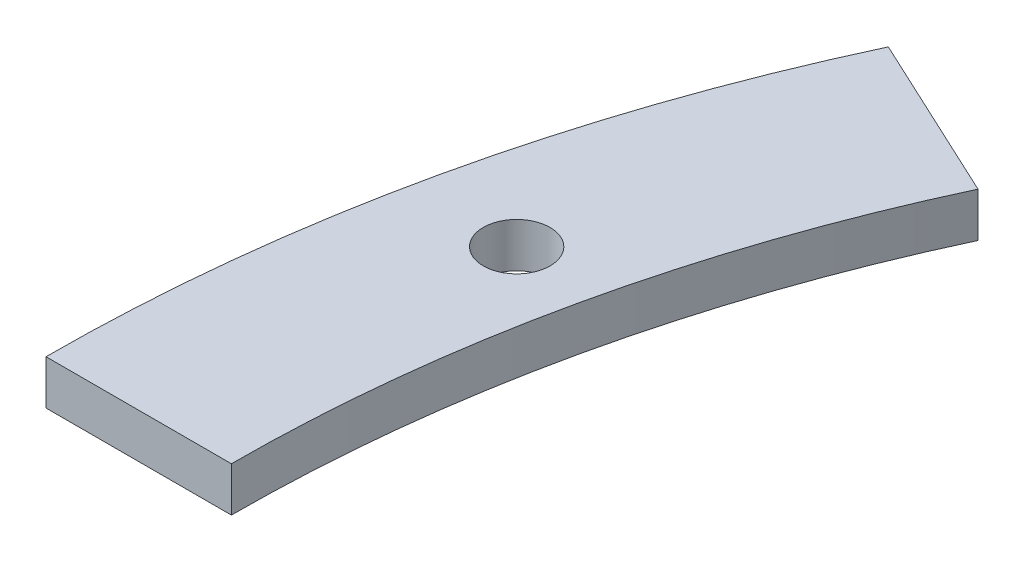
SolidWorks part; units mm, degrees
material "ABS"
ref_plane "Piano frontale" through (0, 0, 0) normal (0, 0, 1) x (1, 0, 0)
ref_plane "Piano superiore" through (0, 0, 0) normal (0, 1, 0) x (1, 0, 0)
ref_plane "Piano destro" through (0, 0, 0) normal (1, 0, 0) x (0, 0, -1)
sketch "Schizzo1" plane through (0, 0, 0) normal (0, 1, 0) x (1, 0, 0)
  line L0 (0, 0) -> (-110, 0) construction
  line L1 (0, 0) -> (-99.6939, 46.488) construction
  line L2 (-99.6939, 46.488) -> (-88.365, 41.2053)
  line L3 (-110, 0) -> (-97.5, 0)
  arc A0 (-88.365, 41.2053) -> (-97.5, 0) centre (0, 0) ccw
  arc A1 (-99.6939, 46.488) -> (-110, 0) centre (0, 0) ccw
  dimension "D1" = 195
  dimension "D2" = 220
  dimension "D3" = 25
extrude "Estrusione-Estrusione1" add sketch "Schizzo1" along normal blind 3
hole_wizard "Foro per Vite M4-1" positions "Schizzo2" profile "Schizzo3" hole size "M4" standard "DIN"
sketch "Schizzo2" plane through (0, 3, 0) normal (0, 1, 0) x (1, 0, 0)
  line L0 (-100.5585, 22.2933) -> (0, 0) construction
  line L2 (0, 0) -> (-128.8063, 0) construction
  point P0 (-100.5585, 22.2933)
  dimension "D1" = 103
  dimension "D2" = 12.5
sketch "Schizzo3" plane through (-100.5585, 3, -22.2933) normal (1, 0, 0) x (0, 0, 1)
  line L0 (0, 0) -> (0, 10.3519)
  line L1 (0, 10.3519) -> (2.25, 9)
  line L2 (2.25, 9) -> (2.25, 0)
  line L5 (2.25, 0) -> (0, 0)
  line L10 (0, 10.3519) -> (-2.25, 9) construction
  line L11 (0, -6.35) -> (0, 107.95) construction
  dimension "Hole Dia." = 4.5
  dimension "Hole Depth" = 9
  dimension "Drill Angle" = 118
